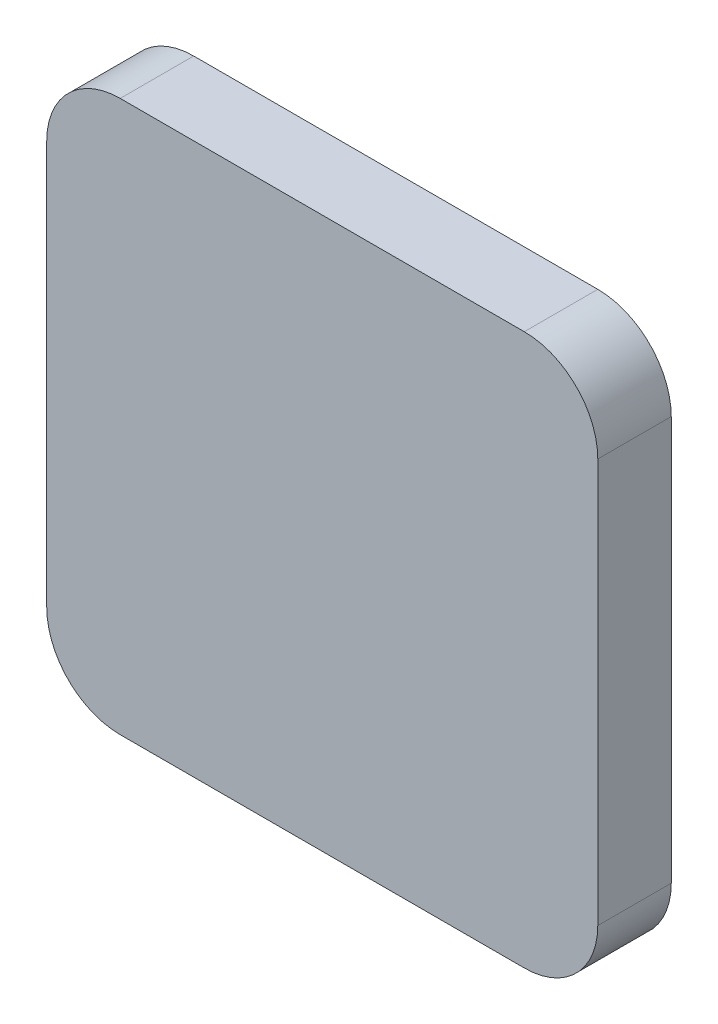
SolidWorks part; units mm, degrees
ref_plane "前视基准面" through (0, 0, 0) normal (0, 0, 1) x (1, 0, 0)
ref_plane "上视基准面" through (0, 0, 0) normal (0, 1, 0) x (1, 0, 0)
ref_plane "右视基准面" through (0, 0, 0) normal (1, 0, 0) x (0, 0, -1)
sketch "草图1" plane through (0, 0, 0) normal (0, 0, 1) x (1, 0, 0)
  line L1 (-30.7017, -8.7229) -> (-19.7017, -8.7229)
  line L2 (-32.7017, -10.7229) -> (-32.7017, -21.7229)
  line L3 (-30.7017, -23.7229) -> (-19.7017, -23.7229)
  line L4 (-17.7017, -10.7229) -> (-17.7017, -21.7229)
  arc A0 (-17.7017, -21.7229) -> (-19.7017, -23.7229) centre (-19.7017, -21.7229) cw
  arc A1 (-30.7017, -23.7229) -> (-32.7017, -21.7229) centre (-30.7017, -21.7229) cw
  arc A2 (-32.7017, -10.7229) -> (-30.7017, -8.7229) centre (-30.7017, -10.7229) cw
  arc A3 (-19.7017, -8.7229) -> (-17.7017, -10.7229) centre (-19.7017, -10.7229) cw
  dimension "D1" = 2
extrude "凸台-拉伸1" add sketch "草图1" along normal blind 2
ref_plane "基准面4" through (0, 0, 2) normal (0, 0, 1) x (1, 0, 0)
